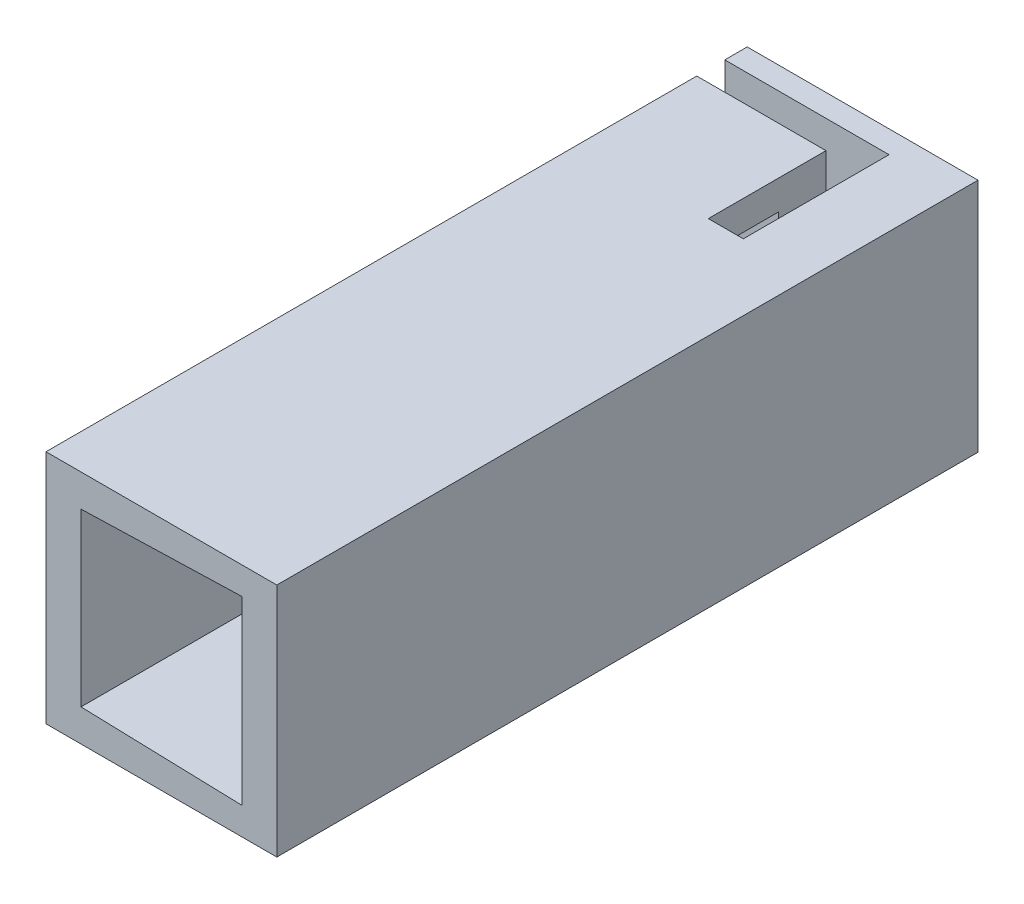
SolidWorks part; units mm, degrees
ref_plane "Front Plane" through (0, 0, 0) normal (0, 0, 1) x (1, 0, 0)
ref_plane "Top Plane" through (0, 0, 0) normal (0, 1, 0) x (1, 0, 0)
ref_plane "Right Plane" through (0, 0, 0) normal (1, 0, 0) x (0, 0, -1)
sketch "Sketch2" plane through (0, 0, 0) normal (0, 0, 1) x (1, 0, 0)
  line L0 (-5, 3.909) -> (-5, 29.729)
  line L1 (-27.95, 29.0442) -> (-5, 29.729)
  line L2 (-27.95, 4.5938) -> (-5, 3.909)
  line L3 (-27.95, 29.0442) -> (-27.95, 4.5938)
  line L5 (-32.95, 33.638) -> (0, 33.638)
  line L6 (-32.95, 33.638) -> (-32.95, 0)
  line L7 (-32.95, 0) -> (0, 0)
  line L8 (0, 33.638) -> (0, 0)
  line L9 (-16.475, 0) -> (-16.475, 33.638) construction
  line L10 (-32.95, 16.819) -> (0, 16.819) construction
  point P2 (-16.475, 16.819)
extrude "Boss-Extrude1" add sketch "Sketch2" along normal blind 86.1
sketch "Sketch4" plane through (0, 0, 0) normal (0, 1, 0) x (1, 0, 0)
  line L1 (0, 0) -> (-32.95, 0)
  line L2 (0, 0) -> (0, 14)
  line L3 (0, 14) -> (-32.95, 14)
  line L4 (-32.95, 0) -> (-32.95, 14)
sketch "Sketch5" plane through (0, 33.638, 0) normal (0, 1, 0) x (1, 0, 0)
  line L0 (0, 0) -> (-9.25, 0) construction
  line L3 (-9.25, 0) -> (-14.75, 0)
  line L4 (-9.5, 0) -> (-9.5, 7.05)
  line L5 (-9.5, 6.8) -> (-14.5, 6.8)
  line L6 (-14.5, 0) -> (-14.5, 6.8)
  line L7 (-32.95, 6.8) -> (-9.5, 6.8)
  line L8 (-32.95, 6.8) -> (-32.95, 10.8)
  line L9 (-32.95, 10.8) -> (-9.5, 10.8)
  line L10 (-9.5, 6.8) -> (-9.5, 10.8)
extrude "Boss-Extrude3" add sketch "Sketch4" along normal up to vertex (33.638 mm away) separate body up to point (0, 33.638, 0)
extrude "Cut-Extrude1" cut sketch "Sketch5" against normal blind 6 and the other way blind 27.1 from vertex at -16.819 contours L6 L3 L4 L5 | L5 L10 L9 L8 L7 starting at point (0, 16.819, 0)
combine bodies "Combine1" operation type add bodies to combine 103 106
sketch "Sketch6" plane through (0, 33.638, 0) normal (0, 1, 0) x (1, 0, 0)
  line L1 (-9.5, 0) -> (-14.5, 0)
  line L2 (-9.5, 0) -> (-9.5, -10)
  line L3 (-9.5, -10) -> (-14.5, -10)
  line L4 (-14.5, 0) -> (-14.5, -10)
extrude "Cut-Extrude2" cut sketch "Sketch6" against normal up to next
